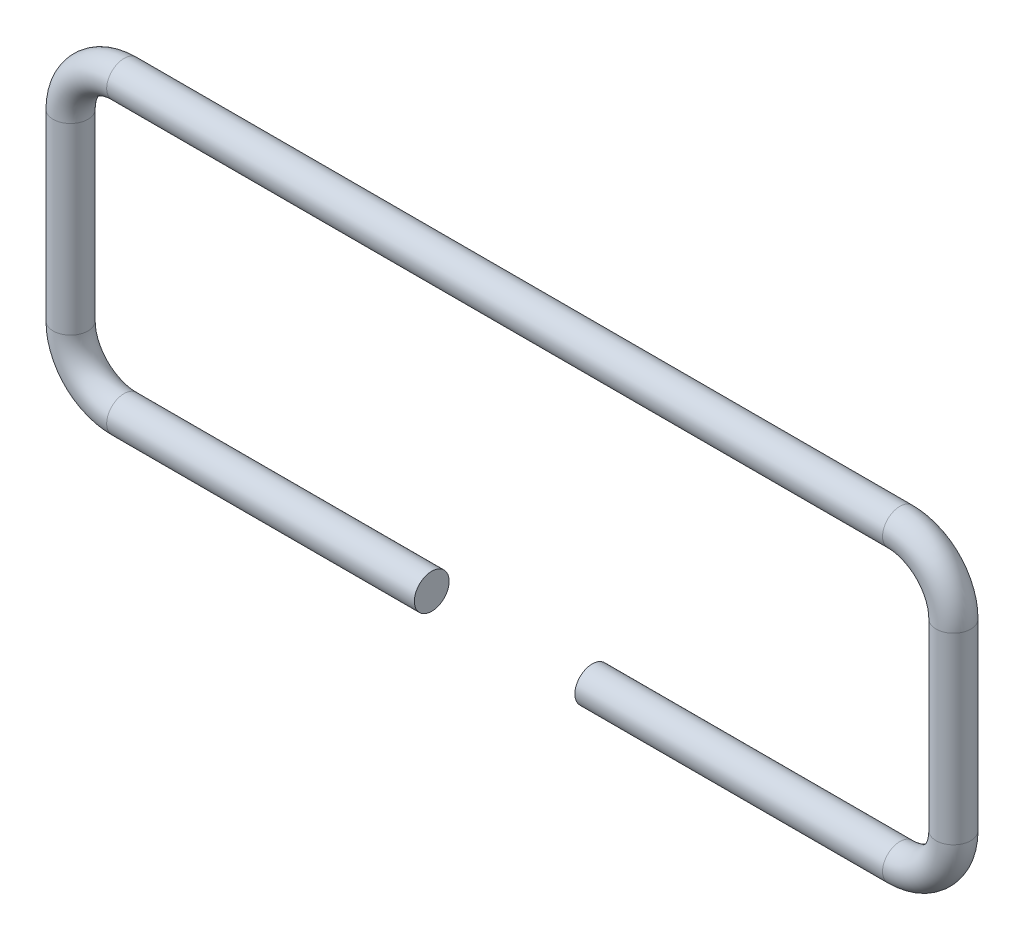
SolidWorks part; units mm, degrees
ref_plane "Front Plane" through (0, 0, 0) normal (0, 0, 1) x (1, 0, 0)
ref_plane "Top Plane" through (0, 0, 0) normal (0, 1, 0) x (1, 0, 0)
ref_plane "Right Plane" through (0, 0, 0) normal (1, 0, 0) x (0, 0, -1)
sketch "Sketch1" plane through (0, 0, 0) normal (0, 0, 1) x (1, 0, 0)
  line L0 (0, 0) -> (6.6502, 0) construction
  line L1 (-14.5, 5.425) -> (14.5, 5.425)
  line L2 (-16.5, 3.425) -> (-16.5, -3.425)
  line L3 (-14.5, -5.425) -> (-3, -5.425)
  line L4 (16.5, 3.425) -> (16.5, -3.425)
  line L5 (0, 0) -> (0, 2.6158) construction
  line L7 (0, -5.425) -> (-3, -5.425) construction
  line L8 (3, -5.425) -> (14.5, -5.425)
  arc A0 (-14.5, 5.425) -> (-16.5, 3.425) centre (-14.5, 3.425) ccw
  arc A1 (14.5, -5.425) -> (16.5, -3.425) centre (14.5, -3.425) ccw
  arc A2 (14.5, 5.425) -> (16.5, 3.425) centre (14.5, 3.425) cw
  arc A3 (-16.5, -3.425) -> (-14.5, -5.425) centre (-14.5, -3.425) ccw
  point P20 (-3, -5.425)
  dimension "D3" = 2
  dimension "D4" = 2
  dimension "D1" = 10.85
  dimension "D2" = 33
  dimension "D5" = 3
  dimension "D6" = 3
ref_plane "Plane1" through (-3, 0, 0) normal (1, 0, 0) x (0, 0, -1)
sketch "Sketch2" plane through (-3, 0, 0) normal (1, 0, 0) x (0, 0, -1)
  line L0 (0, -3.425) -> (0, -5.425) construction
  circle A0 centre (0, -5.425) radius 0.65
  point P4 (0, -3.7301)
  point P5 (0, -3)
  dimension "D1" = 1.3
sweep "Sweep2" add profiles "Sketch2" path "Sketch1"
